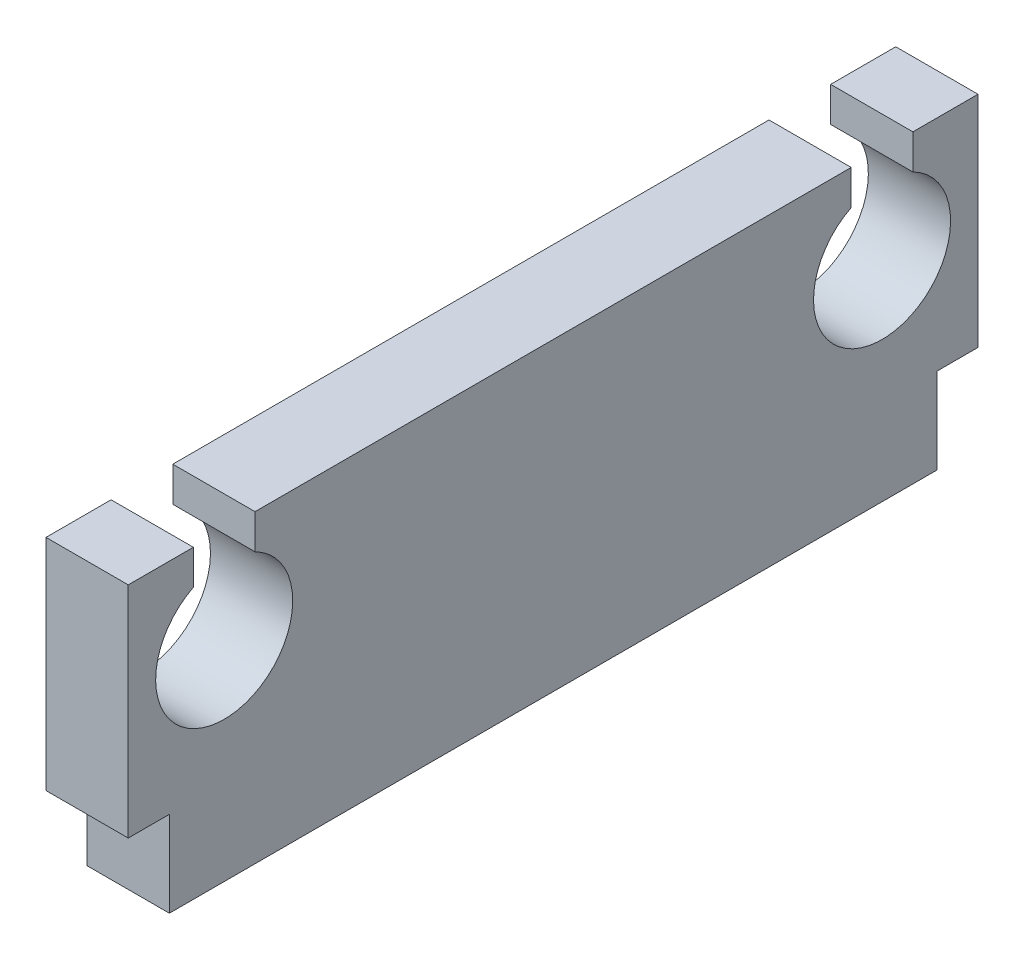
SolidWorks part; units mm, degrees
ref_plane "Front Plane" through (0, 0, 0) normal (0, 0, 1) x (1, 0, 0)
ref_plane "Top Plane" through (0, 0, 0) normal (0, 1, 0) x (1, 0, 0)
ref_plane "Right Plane" through (0, 0, 0) normal (1, 0, 0) x (0, 0, -1)
sketch "Sketch1" plane through (0, 0, 0) normal (0, 1, 0) x (1, 0, 0)
  line L1 (0, 0) -> (6, 0)
  line L2 (0, 0) -> (0, 56)
  line L3 (0, 56) -> (6, 56)
  line L4 (6, 0) -> (6, 56)
  dimension "D1" = 6
  dimension "D2" = 56
extrude "Boss-Extrude1" add sketch "Sketch1" along normal blind 22.25
ref_plane "Plane1" through (0, 0, -28) normal (0, 0, -1) x (-1, 0, 0)
sketch "Sketch6" plane through (0, 0, -56) normal (0, 0, -1) x (-1, 0, 0)
  line L0 (0, 22.25) -> (0, 0) construction
  line L1 (-6, 22.25) -> (0, 22.25)
  line L2 (-6, 22.25) -> (-6, 6.25)
  line L3 (-6, 6.25) -> (0, 6.25)
  line L4 (0, 22.25) -> (0, 6.25)
  dimension "D1" = 16
extrude "Boss-Extrude3" add sketch "Sketch6" along normal blind 3
mirror "Mirror3" about plane through (0, 0, -28) normal (0, 0, -1) of "Boss-Extrude3"
sketch "Sketch7" plane through (0, 0, 0) normal (-1, 0, 0) x (0, 0, 1)
  line L0 (-59, 22.25) -> (3, 22.25) construction
  line L5 (-59, 6.25) -> (-59, 22.25) construction
  line L6 (-28, 22.25) -> (-28, 0) construction
  line L8 (-54.25, 19.7151) -> (-54.25, 24.7151)
  line L9 (-54.25, 24.7151) -> (-49.75, 24.7151)
  line L10 (-49.75, 19.7151) -> (-49.75, 24.7151)
  line L11 (-56, 0) -> (0, 0) construction
  line L12 (-6.25, 19.7151) -> (-6.25, 24.7151)
  line L13 (-1.75, 24.7151) -> (-6.25, 24.7151)
  line L14 (-1.75, 19.7151) -> (-1.75, 24.7151)
  arc A0 (-54.25, 19.7151) -> (-49.75, 19.7151) centre (-52, 15.25) ccw
  arc A1 (-1.75, 19.7151) -> (-6.25, 19.7151) centre (-4, 15.25) cw
  point P6 (-52, 15.25)
  dimension "D3" = 2.25
  dimension "D4" = 10
  dimension "D1" = 7
  dimension "D2" = 7
  dimension "D5" = 2.25
  dimension "D6" = 5
extrude "Cut-Extrude1" cut sketch "Sketch7" against normal up to surface (6 mm away) up to face at (6, 8.6875, -28)
